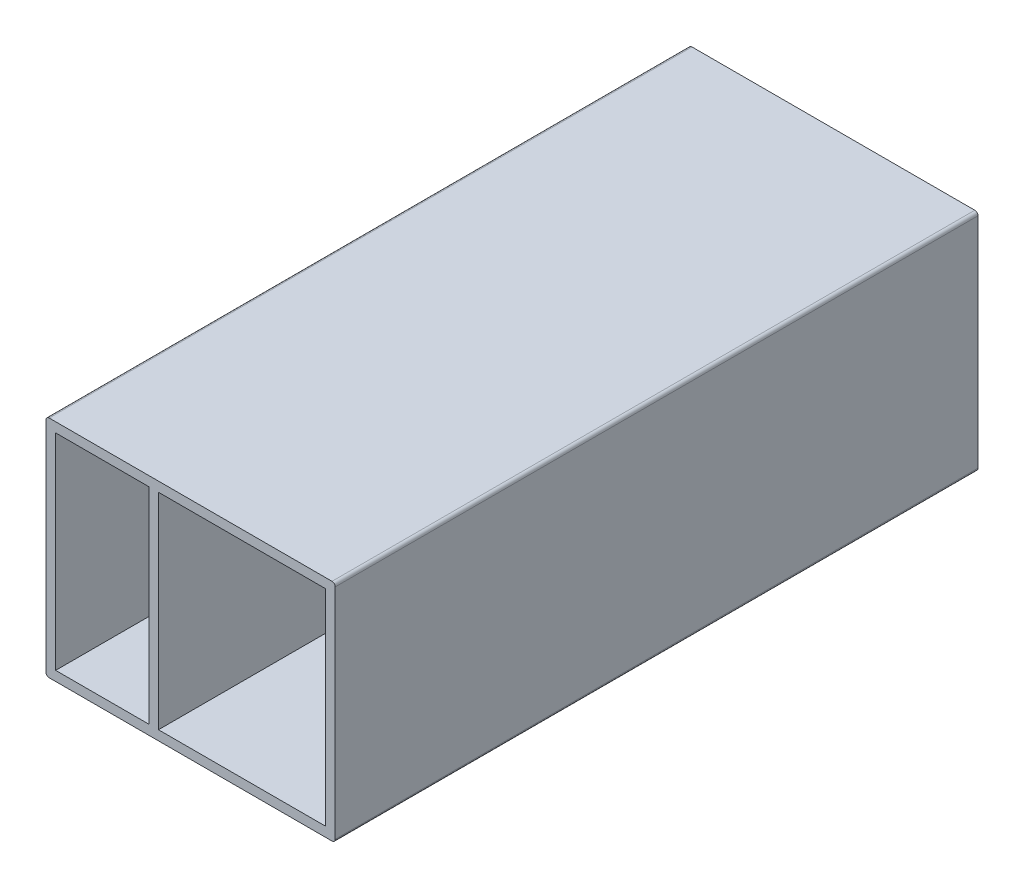
SolidWorks part; units mm, degrees
material "Faia"
ref_plane "Plano frontal" through (0, 0, 0) normal (0, 0, 1) x (1, 0, 0)
ref_plane "Plano superior" through (0, 0, 0) normal (0, 1, 0) x (1, 0, 0)
ref_plane "Plano direito" through (0, 0, 0) normal (1, 0, 0) x (0, 0, -1)
sketch "Esboço1" plane through (0, 0, 0) normal (0, 0, 1) x (1, 0, 0)
  line L0 (0, 35) -> (0, -35) construction
  line L1 (-45, -35) -> (45, -35)
  line L2 (-45, -35) -> (-45, 35)
  line L3 (-45, 35) -> (45, 35)
  line L4 (45, -35) -> (45, 35)
  line L5 (-45, -35) -> (45, 35) construction
  line L6 (-45, 35) -> (45, -35) construction
  line L7 (-42, -32) -> (-13, -32)
  line L8 (-42, -32) -> (-42, 32)
  line L9 (-42, 32) -> (-13, 32)
  line L10 (42, -32) -> (42, 32)
  line L11 (-42, -32) -> (42, 32) construction
  line L12 (-42, 32) -> (42, -32) construction
  line L13 (81.4345, 0) -> (-75.8693, 0) construction
  line L14 (-13, 32) -> (-13, -32)
  line L15 (-10, 32) -> (-10, -32)
  line L16 (-13, 50.9668) -> (-13, -52.9661) construction
  line L17 (-10, 50.9668) -> (-10, -52.9661) construction
  line L18 (-10, 32) -> (42, 32)
  line L19 (-10, -32) -> (42, -32)
  point P0 (0, 0)
  point P6 (0, 0)
  dimension "D1" = 90
  dimension "D2" = 70
  dimension "D3" = 84
  dimension "D4" = 64
  dimension "D5" = 3
extrude "Ressalto-extrusão1" add sketch "Esboço1" along normal blind 200
fillet "Filete1" radius 1 4 edges at (-45, -35, 100) (45, -35, 100) (45, 35, 100) (-45, 35, 100)
sketch "Esboço4" plane through (-10, 0, 0) normal (1, 0, 0) x (0, 0, -1)
  line L4 (-92, 19.6938) -> (-92, 17.6938) construction
  line L8 (-92, -14.8977) -> (-92, -16.8977) construction
  circle A0 centre (-100, 0) radius 4.75
  circle A3 centre (-92, 19.6938) radius 2
  circle A4 centre (-92, -16.8977) radius 2
  point P11 (-92, 1.3981)
  dimension "D1" = 9.5
extrude "Corte-extrusão1" cut sketch "Esboço4" against normal blind 3
sketch "Esboço5" plane through (0, 0, 0) normal (0, 0, -1) x (-1, 0, 0)
  line L1 (48.712, 25) -> (38.4024, 25)
  line L2 (48.712, 25) -> (48.712, -25)
  line L3 (48.712, -25) -> (38.4024, -25)
  line L4 (38.4024, 25) -> (38.4024, -25)
  line L5 (48.712, 25) -> (38.4024, -25) construction
  line L6 (48.712, -25) -> (38.4024, 25) construction
  line L7 (44, -35) -> (-44, -35) construction
  point P0 (43.5572, 0)
  dimension "D1" = 50
  dimension "D2" = 10
extrude "Corte-extrusão2" cut sketch "Esboço5" against normal blind 5 contours L2 L3 L4 L1
